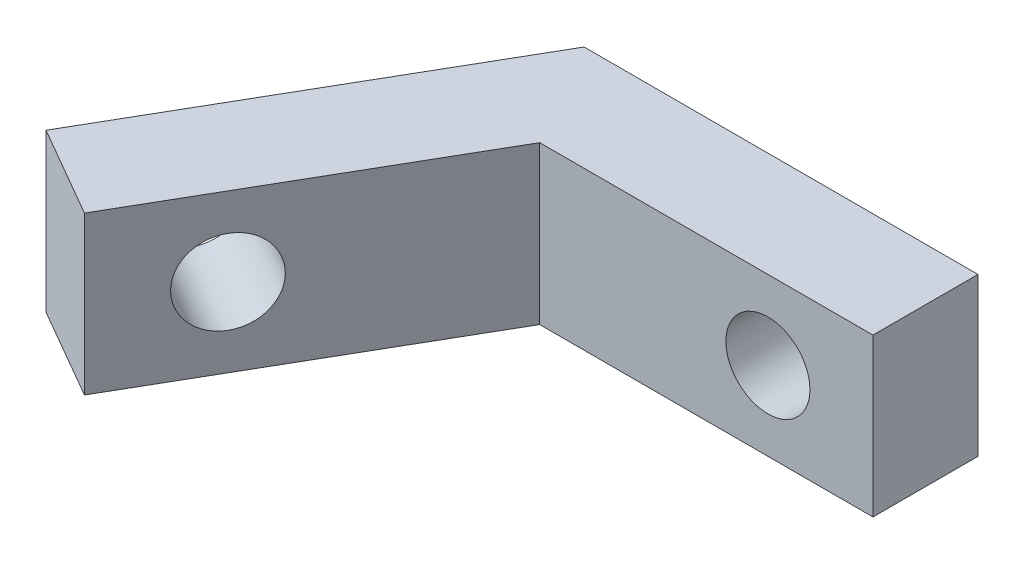
SolidWorks part; units mm, degrees
ref_plane "前视基准面" through (0, 0, 0) normal (0, 0, 1) x (1, 0, 0)
ref_plane "上视基准面" through (0, 0, 0) normal (0, 1, 0) x (1, 0, 0)
ref_plane "右视基准面" through (0, 0, 0) normal (1, 0, 0) x (0, 0, -1)
sketch "草图1" plane through (0, 0, 0) normal (0, 1, 0) x (1, 0, 0)
  line L0 (0, 0) -> (15, 0)
  line L1 (15, 0) -> (15, -4)
  line L2 (15, -4) -> (2.3094, -4)
  line L3 (2.3094, -4) -> (-4.0359, -14.9904)
  line L4 (-4.0359, -14.9904) -> (-7.5, -12.9904)
  line L5 (-7.5, -12.9904) -> (0, 0)
  dimension "D1" = 4
  dimension "D2" = 4
  dimension "D3" = 120
  dimension "D4" = 15
  dimension "D5" = 15
extrude "凸台-拉伸1" add sketch "草图1" along normal blind 6
ref_plane "基准面1" through (0, 0, 0) normal (-0.866, 0, 0.5) x (0.5, 0, 0.866)
sketch "草图2" plane through (0, 0, 0) normal (-0.866, 0, -0.5) x (-0.5, 0, 0.866)
  line L0 (15, 3) -> (4.1317, 3) construction
  line L1 (15, 6) -> (15, 0) construction
  circle A0 centre (11, 3) radius 1.6
  dimension "D1" = 3.2
  dimension "D2" = 4
extrude "切除-拉伸1" cut sketch "草图2" against normal up to next and the other way through all
mirror "镜向1" about plane through (0, 0, 0) normal (-0.866, 0, 0.5) of "切除-拉伸1"
